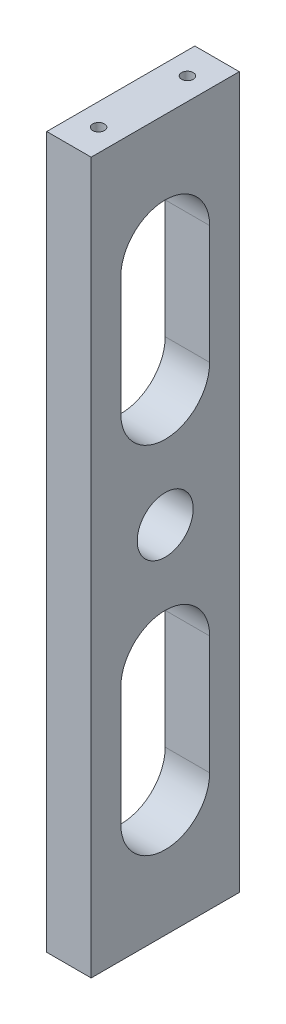
SolidWorks part; units mm, degrees
material "6061 Alloy"
ref_plane "Front Plane" through (0, 0, 0) normal (0, 0, 1) x (1, 0, 0)
ref_plane "Top Plane" through (0, 0, 0) normal (0, 1, 0) x (1, 0, 0)
ref_plane "Right Plane" through (0, 0, 0) normal (1, 0, 0) x (0, 0, -1)
sketch "Sketch1" plane through (0, 0, 0) normal (1, 0, 0) x (0, 0, -1)
  line L1 (-15.875, -76.2) -> (15.875, -76.2)
  line L2 (-15.875, -76.2) -> (-15.875, 76.2)
  line L3 (-15.875, 76.2) -> (15.875, 76.2)
  line L4 (15.875, -76.2) -> (15.875, 76.2)
  line L5 (-15.875, -76.2) -> (15.875, 76.2) construction
  line L6 (-15.875, 76.2) -> (15.875, -76.2) construction
  point P0 (0, 0)
  dimension "D1" = 31.75
  dimension "D2" = 152.4
extrude "Boss-Extrude1" add sketch "Sketch1" along normal mid plane 9.525
sketch "Sketch2" plane through (0, 76.2, 0) normal (0, 1, 0) x (1, 0, 0)
  line L0 (0, 9.525) -> (0, -9.525) construction
  line L1 (-4.7625, 15.875) -> (-4.7625, -15.875) construction
  line L2 (4.7625, 15.875) -> (-4.7625, 15.875) construction
  point P2 (0, 0)
  point P5 (-4.7625, 0)
  point P8 (0, 15.875)
  point P10 (0, 9.525)
  point P11 (0, -9.525)
  dimension "D1" = 19.05
hole_wizard "M3x0.5 Tapped Hole1" positions "Sketch3" profile "Sketch4" tap size "M3x0.5" standard "ANSI Metric"
sketch "Sketch3" plane through (0, 76.2, 0) normal (0, 1, 0) x (1, 0, 0)
  point P0 (0, 9.525)
  point P3 (0, -9.525)
sketch "Sketch4" plane through (0, 76.2, -9.525) normal (1, 0, 0) x (0, 0, 1)
  line L0 (0, 0) -> (0, 13.4511)
  line L1 (0, 13.4511) -> (1.25, 12.7)
  line L2 (1.25, 12.7) -> (1.25, 0)
  line L5 (1.25, 0) -> (0, 0)
  line L10 (0, 13.4511) -> (-1.25, 12.7) construction
  line L11 (0, -6.35) -> (0, 107.95) construction
  dimension "Tap Drill Dia." = 2.5
  dimension "Tap Drill Depth" = 12.7
  dimension "Drill Angle" = 118
cosmetic thread "Hole Thread1" parameters "D1"=6.096, "D2"=3
cosmetic thread "Hole Thread2" parameters "D1"=6.096, "D2"=3
mirror "Mirror1" about plane through (0, 0, 0) normal (0, 1, 0) of "M3x0.5 Tapped Hole1"
cosmetic thread "Hole Thread3" parameters "D1"=6.096, "D2"=3
cosmetic thread "Hole Thread4" parameters "D1"=6.096, "D2"=3
sketch "Sketch5" plane through (4.7625, 0, 0) normal (1, 0, 0) x (0, 0, -1)
  point P0 (0, 0)
hole_wizard "Ø12.0mm Dowel Hole1" positions "Sketch6" profile "Sketch8" hole size "Ø12.0" standard "ANSI Metric" end condition through all
sketch "Sketch6" plane through (4.7625, 0, 0) normal (1, 0, 0) x (0, 0, -1)
  point P0 (0, 0)
sketch "Sketch8" plane through (4.7625, 0, 0) normal (0, 1, 0) x (0, 0, -1)
  line L0 (0, 0) -> (0, 9.525)
  line L1 (0, 9.525) -> (6, 9.525)
  line L2 (6, 9.525) -> (6, 0)
  line L5 (6, 0) -> (0, 0)
  line L11 (0, -6.35) -> (0, 107.95) construction
  dimension "Thru Hole Dia." = 12
  dimension "Thru Hole Depth" = 9.525
sketch "Sketch9" plane through (4.7625, 0, 0) normal (1, 0, 0) x (0, 0, -1)
  line L0 (0, 50.8) -> (0, 25.4) construction
  line L1 (0, 55) -> (0, -55) construction
  line L2 (9.525, 50.8) -> (9.525, 25.4)
  line L3 (-9.525, 50.8) -> (-9.525, 25.4)
  line L4 (0, -25.4) -> (0, -50.8) construction
  line L5 (9.525, -25.4) -> (9.525, -50.8)
  line L6 (-9.525, -25.4) -> (-9.525, -50.8)
  line L7 (0, 25.4) -> (0, -25.4)
  line L8 (55, 0) -> (-55, 0) construction
  arc A0 (9.525, 50.8) -> (-9.525, 50.8) centre (0, 50.8) ccw
  arc A1 (-9.525, 25.4) -> (9.525, 25.4) centre (0, 25.4) ccw
  arc A2 (9.525, -25.4) -> (-9.525, -25.4) centre (0, -25.4) ccw
  arc A3 (-9.525, -50.8) -> (9.525, -50.8) centre (0, -50.8) ccw
  point P5 (0, 38.1)
  point P10 (0, -38.1)
  point P19 (0, 0)
  dimension "D1" = 25.4
  dimension "D2" = 19.05
  dimension "D3" = 25.4
extrude "Cut-Extrude1" cut sketch "Sketch9" against normal through all
